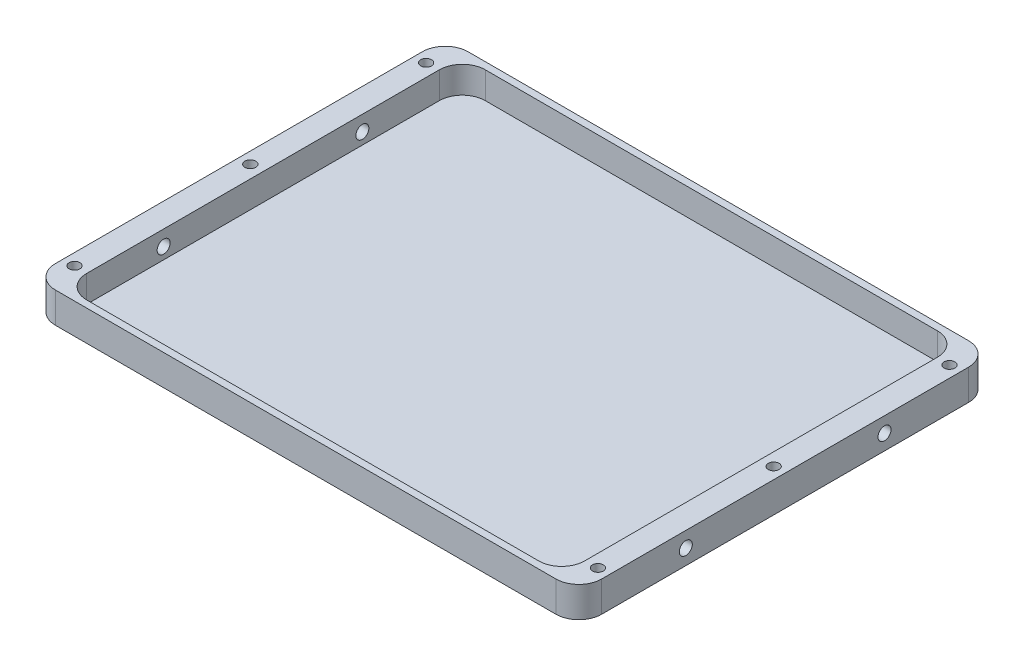
SolidWorks part; units mm, degrees
ref_plane "Front Plane" through (0, 0, 0) normal (0, 0, 1) x (1, 0, 0)
ref_plane "Top Plane" through (0, 0, 0) normal (0, 1, 0) x (1, 0, 0)
ref_plane "Right Plane" through (0, 0, 0) normal (1, 0, 0) x (0, 0, -1)
sketch "Sketch1" plane through (0, 0, 0) normal (0, 1, 0) x (1, 0, 0)
  line L1 (0, 0) -> (226.949, 0)
  line L2 (0, 0) -> (0, 171.45)
  line L3 (0, 171.45) -> (226.949, 171.45)
  line L4 (226.949, 0) -> (226.949, 171.45)
  dimension "D1" = 171.45
  dimension "D2" = 226.949
extrude "Boss-Extrude1" add sketch "Sketch1" along normal blind 12.7
sketch "Sketch2" plane through (0, 12.7, 0) normal (0, 1, 0) x (1, 0, 0)
  line L0 (113.4745, 171.45) -> (113.4745, 0) construction
  line L1 (19.558, 2.921) -> (207.391, 2.921)
  line L2 (10.033, 12.446) -> (10.033, 159.004)
  line L3 (19.558, 168.529) -> (207.391, 168.529)
  line L4 (216.916, 12.446) -> (216.916, 159.004)
  line L5 (10.033, 2.921) -> (216.916, 168.529) construction
  line L6 (10.033, 168.529) -> (216.916, 2.921) construction
  line L7 (226.949, 171.45) -> (0, 171.45) construction
  line L8 (0, 0) -> (226.949, 0) construction
  line L9 (0, 85.725) -> (226.949, 85.725) construction
  line L10 (0, 171.45) -> (0, 0) construction
  line L11 (226.949, 0) -> (226.949, 171.45) construction
  arc A0 (207.391, 168.529) -> (216.916, 159.004) centre (207.391, 159.004) cw
  arc A1 (207.391, 2.921) -> (216.916, 12.446) centre (207.391, 12.446) ccw
  arc A2 (19.558, 2.921) -> (10.033, 12.446) centre (19.558, 12.446) cw
  arc A3 (10.033, 159.004) -> (19.558, 168.529) centre (19.558, 159.004) cw
  point P0 (113.4745, 85.725)
  dimension "D3" = 9.525
  dimension "D1" = 165.608
  dimension "D2" = 206.883
extrude "Cut-Extrude1" cut sketch "Sketch2" against normal blind 11.1125
ref_plane "Plane1" through (113.4745, 0, 0) normal (1, 0, 0) x (0, 0, -1)
hole_wizard "1/4-28 Tapped Hole1" positions "Sketch10" profile "Sketch11" tap size "1/4-28" standard "Ansi Inch"
sketch "Sketch10" plane through (0, 0, 0) normal (-1, 0, 0) x (0, 0, 1)
  line L0 (-171.45, 6.35) -> (0, 6.35) construction
  line L1 (-171.45, 12.7) -> (-171.45, 0) construction
  line L2 (0, 12.7) -> (0, 0) construction
  point P0 (-127, 6.35)
  point P1 (-44.45, 6.35)
  dimension "D1" = 44.45
  dimension "D2" = 44.45
sketch "Sketch11" plane through (0, 6.35, -127) normal (0, 1, 0) x (0, 0, 1)
  line L0 (0, 0) -> (0, 226.949)
  line L1 (0, 226.949) -> (2.7051, 226.949)
  line L2 (2.7051, 226.949) -> (2.7051, 0)
  line L5 (2.7051, 0) -> (0, 0)
  line L11 (0, -6.35) -> (0, 107.95) construction
  dimension "Thru Tap Drill Dia." = 5.4102
  dimension "Thru Tap Drill Depth" = 226.949
cosmetic thread "Hole Thread4" parameters "D2"=6.35
cosmetic thread "Hole Thread5" parameters "D2"=6.35
sketch "Sketch12" plane through (0, 0, 0) normal (0, -1, 0) x (1, 0, 0)
  line L0 (4.7625, 0) -> (4.7625, -171.45) construction
  line L1 (0, 0) -> (226.949, 0) construction
  line L2 (226.949, -171.45) -> (0, -171.45) construction
  line L3 (0, -171.45) -> (0, 0) construction
  dimension "D1" = 4.7625
hole_wizard "CSK for #8 Flat Head Socket Cap Screw1" positions "Sketch14" profile "Sketch13" countersink size "#8" standard "Ansi Inch" end condition through all
sketch "Sketch14" plane through (0, 0, 0) normal (0, -1, 0) x (1, 0, 0)
  line L0 (4.7625, 0) -> (4.7625, -171.45) construction
  line L1 (0, 0) -> (226.949, 0) construction
  line L2 (226.949, -171.45) -> (0, -171.45) construction
  point P0 (4.7625, -12.7)
  point P1 (4.7625, -85.725)
  point P5 (4.7625, -158.75)
  dimension "D1" = 12.7
  dimension "D2" = 12.7
sketch "Sketch13" plane through (4.7625, 0, -12.7) normal (1, 0, 0) x (0, 0, -1)
  line L0 (0, 0) -> (0, 12.7)
  line L1 (0, 12.7) -> (2.2479, 12.7)
  line L2 (2.2479, 12.7) -> (2.2479, 2.659)
  line L3 (2.2479, 2.659) -> (4.5593, 0)
  line L5 (4.5593, 0) -> (0, 0)
  line L6 (-2.2479, 2.659) -> (-4.5593, 0) construction
  line L11 (0, -6.35) -> (0, 107.95) construction
  dimension "Thru Hole Dia." = 4.4958
  dimension "Thru Hole Depth" = 12.7
  dimension "Near C'Sink Dia." = 9.1186
  dimension "Near C'Sink Angle" = 82
mirror "Mirror1" about plane through (113.4745, 0, 0) normal (1, 0, 0) of "CSK for #8 Flat Head Socket Cap Screw1", "1/4-28 Tapped Hole1"
fillet "Fillet1" radius 9.525 4 edges at (0, 6.35, -171.45) (0, 6.35, 0) (226.949, 6.35, 0) (226.949, 6.35, -171.45)
